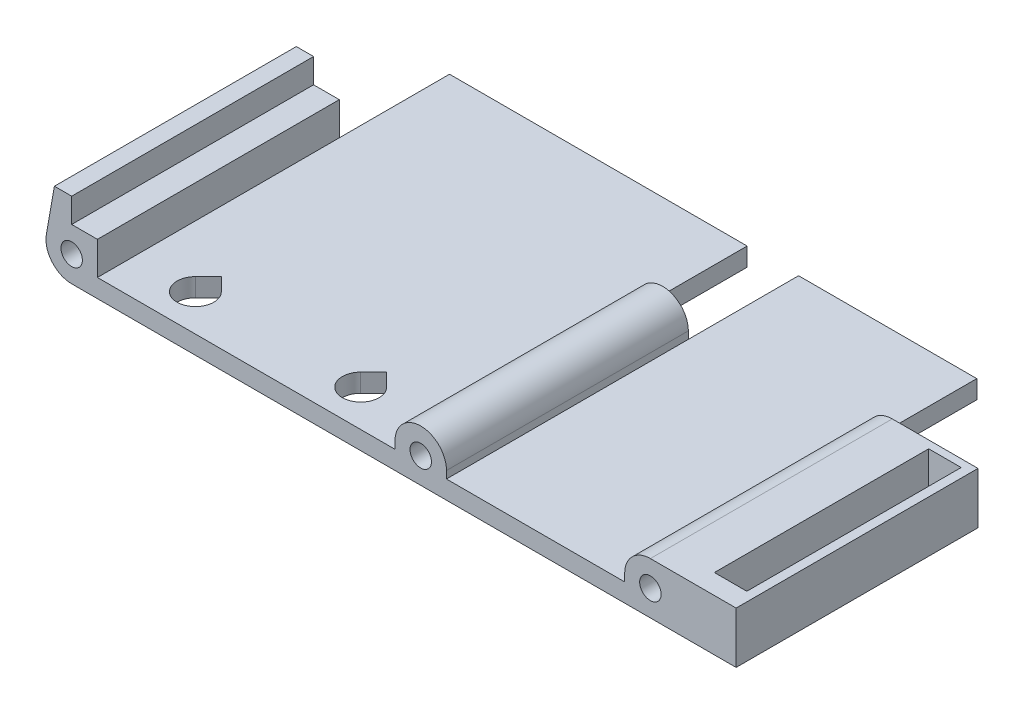
SolidWorks part; units mm, degrees
material "Custom Plastic"
ref_plane "Front Plane" through (0, 0, 0) normal (0, 0, 1) x (1, 0, 0)
ref_plane "Top Plane" through (0, 0, 0) normal (0, 1, 0) x (1, 0, 0)
ref_plane "Right Plane" through (0, 0, 0) normal (1, 0, 0) x (0, 0, -1)
sketch "Sketch1" plane through (0, 0, 0) normal (0, 0, 1) x (1, 0, 0)
  line L0 (-52.8, -1.2) -> (-4.2, -1.2)
  line L1 (-57, -4.2) -> (41.5, -4.2)
  line L2 (4.2, 0) -> (4.2, -1.2)
  line L3 (37.5, 4.2) -> (41.5, 4.2)
  line L4 (41.5, -4.2) -> (41.5, 4.2)
  line L5 (-4.2, 0) -> (-4.2, -1.2)
  line L6 (33.3, 0) -> (33.3, -1.2)
  line L7 (-52.8, 4.2) -> (-52.8, -1.2)
  line L8 (-57, 4.2) -> (-57, 8.2)
  line L9 (4.2, -1.2) -> (33.3, -1.2)
  line L10 (-57, 8.2) -> (-59.8189, 8.2)
  line L11 (-59.8189, 8.2) -> (-61.1362, 0.7293)
  line L12 (-57, 4.2) -> (-52.8, 4.2)
  circle A0 centre (0, 0) radius 1.75
  circle A1 centre (-57, 0) radius 1.75
  circle A2 centre (37.5, 0) radius 1.75
  arc A3 (-57, -4.2) -> (-61.1362, 0.7293) centre (-57, 0) cw
  arc A4 (37.5, 4.2) -> (33.3, 0) centre (37.5, 0) ccw
  arc A6 (4.2, 0) -> (-4.2, 0) centre (0, 0) ccw
  dimension "D2" = 37.5
  dimension "D3" = 3.5
  dimension "D1" = 57
  dimension "D4" = 4.2
  dimension "D5" = 4
  dimension "D6" = 3
  dimension "D7" = 10
  dimension "D8" = 4
extrude "Boss-Extrude1" add sketch "Sketch1" along normal blind 57.5
sketch "Sketch2" plane through (0, 4.2, 0) normal (0, 1, 0) x (1, 0, 0)
  line L0 (41.5, -57.5) -> (51.5, -57.5)
  line L1 (51.5, -57.5) -> (51.5, -17.5)
  line L2 (51.5, -17.5) -> (41.5, 0)
  line L3 (41.5, -57.5) -> (41.5, 0) construction
  line L4 (41.5, 0) -> (41.5, -57.5)
  dimension "D1" = 10
  dimension "D2" = 40
extrude "Boss-Extrude2" add sketch "Sketch2" against normal up to surface (8.4 mm away) up to face at (-7.75, -4.2, 28.75)
sketch "Sketch3" plane through (0, 4.2, 0) normal (0, 1, 0) x (1, 0, 0)
  line L0 (33.3, -57.5) -> (4.2, -57.5) construction
  line L1 (44.7, -54.25) -> (50, -54.25)
  line L2 (44.7, -54.25) -> (44.7, -19.25)
  line L3 (44.7, -19.25) -> (50, -19.25)
  line L4 (50, -54.25) -> (50, -19.25)
  dimension "D1" = 5.3
  dimension "D2" = 8.5
  dimension "D3" = 3.25
  dimension "D4" = 35
extrude "Cut-Extrude1" cut sketch "Sketch3" against normal offset from surface (5.4 mm away) 3 up to face at (6.1, -4.2, 26.5)
sketch "Sketch4" plane through (0, -1.2, 0) normal (0, 1, 0) x (1, 0, 0)
  line L1 (-45.8, -48.5) -> (-39.8, -48.5) construction
  line L2 (-45.8, -48.5) -> (-45.8, -54.5) construction
  line L3 (-45.8, -54.5) -> (-39.8, -54.5) construction
  line L4 (-39.8, -48.5) -> (-39.8, -54.5) construction
  line L6 (-4.2, -57.5) -> (-52.8, -57.5) construction
  line L7 (-44.9213, -49.3787) -> (-42.8, -47.2574)
  line L8 (-42.8, -47.2574) -> (-40.6787, -49.3787)
  line L9 (-52.8, -57.5) -> (-52.8, 0) construction
  arc A0 (-44.9213, -49.3787) -> (-40.6787, -49.3787) centre (-42.8, -51.5) ccw
  dimension "D1" = 6
  dimension "D2" = 6
  dimension "D3" = 3
  dimension "D4" = 10
extrude "Cut-Extrude2" cut sketch "Sketch4" against normal through all
sketch "Sketch5" plane through (0, 0, 0) normal (0, 0, -1) x (-1, 0, 0)
  line L0 (57, -4.2) -> (-41.5, -4.2) construction
  line L1 (-33.3, -4.2) -> (-51.5, -4.2)
  line L2 (-33.3, -4.2) -> (-33.3, 4.2)
  line L3 (-33.3, 4.2) -> (-51.5, 4.2)
  line L4 (-51.5, -4.2) -> (-51.5, 4.2)
  line L5 (57, 8.2) -> (59.8189, 8.2) construction
  line L6 (-4.2, -4.2) -> (4.2, -4.2)
  line L7 (-4.2, -4.2) -> (-4.2, 4.7374)
  line L8 (-4.2, 4.7374) -> (4.2, 4.7374)
  line L9 (4.2, -4.2) -> (4.2, 4.7374)
  line L10 (52.8, -4.2) -> (62.6756, -4.2)
  line L11 (52.8, -4.2) -> (52.8, 8.2)
  line L12 (52.8, 8.2) -> (62.6756, 8.2)
  line L13 (62.6756, -4.2) -> (62.6756, 8.2)
  line L14 (52.8, -1.2) -> (52.8, 4.2) construction
  line L15 (4.2, 0) -> (4.2, -1.2) construction
  line L16 (-4.2, -1.2) -> (-4.2, 0) construction
  line L17 (-33.3, 0) -> (-33.3, -1.2) construction
extrude "Cut-Extrude3" cut sketch "Sketch5" against normal blind 18
pattern_linear "LPattern1" count 2 spacing 27 along (1, 0, 0) of "Cut-Extrude2"
